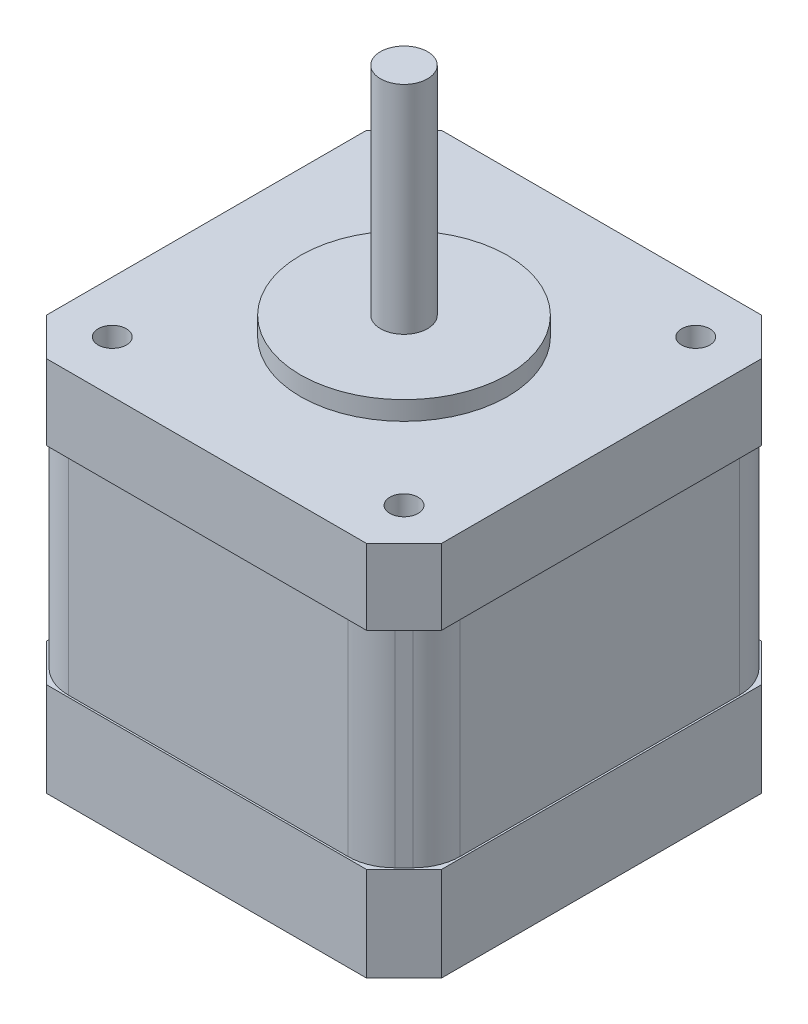
SolidWorks part; units mm, degrees
ref_plane "Front Plane" through (0, 0, 0) normal (0, 0, 1) x (1, 0, 0)
ref_plane "Top Plane" through (0, 0, 0) normal (0, 1, 0) x (1, 0, 0)
ref_plane "Right Plane" through (0, 0, 0) normal (1, 0, 0) x (0, 0, -1)
sketch "Sketch1" plane through (0, 0, 0) normal (0, 1, 0) x (1, 0, 0)
  line L0 (-21, 17) -> (-17, 21)
  line L1 (-17, 21) -> (17, 21)
  line L2 (-21, 17) -> (-21, -17)
  line L3 (-17, -21) -> (17, -21)
  line L4 (21, 17) -> (21, -17)
  line L5 (-21, 21) -> (21, -21) construction
  line L6 (-21, -21) -> (21, 21) construction
  line L7 (-15.5, 15.5) -> (15.5, 15.5) construction
  line L8 (-15.5, 15.5) -> (-15.5, -15.5) construction
  line L9 (-15.5, -15.5) -> (15.5, -15.5) construction
  line L10 (15.5, 15.5) -> (15.5, -15.5) construction
  line L11 (-15.5, 15.5) -> (15.5, -15.5) construction
  line L12 (-15.5, -15.5) -> (15.5, 15.5) construction
  line L13 (17, 21) -> (21, 17)
  line L14 (17, -21) -> (21, -17)
  line L15 (-21, -17) -> (-17, -21)
  line L16 (-20.8, 14.8461) -> (-20.8, -14.8461)
  line L17 (-19.3355, -18.3816) -> (-18.3816, -19.3355)
  line L18 (-14.8461, -20.8) -> (14.8461, -20.8)
  line L19 (18.3816, -19.3355) -> (19.3355, -18.3816)
  line L20 (20.8, 14.8461) -> (20.8, -14.8461)
  line L21 (18.3816, 19.3355) -> (19.3355, 18.3816)
  line L22 (-14.8461, 20.8) -> (14.8461, 20.8)
  line L23 (-19.3355, 18.3816) -> (-18.3816, 19.3355)
  line L24 (16.9172, -20.8) -> (20.8, -16.9172) construction
  line L25 (20.8, 16.9172) -> (20.8, -16.9172) construction
  line L26 (-16.9172, -20.8) -> (16.9172, -20.8) construction
  line L27 (16.9172, 20.8) -> (20.8, 16.9172) construction
  line L28 (-16.9172, 20.8) -> (16.9172, 20.8) construction
  line L29 (-20.8, -16.9172) -> (-16.9172, -20.8) construction
  line L30 (-20.8, 16.9172) -> (-20.8, -16.9172) construction
  line L31 (-20.8, 16.9172) -> (-16.9172, 20.8) construction
  circle A0 centre (-15.5, 15.5) radius 1.5
  circle A1 centre (15.5, 15.5) radius 1.5
  circle A2 centre (15.5, -15.5) radius 1.5
  circle A3 centre (-15.5, -15.5) radius 1.5
  circle A4 centre (0, 0) radius 2.5
  circle A5 centre (0, 0) radius 11
  arc A6 (19.3355, -18.3816) -> (20.8, -14.8461) centre (15.8, -14.8461) ccw
  arc A7 (14.8461, -20.8) -> (18.3816, -19.3355) centre (14.8461, -15.8) ccw
  arc A8 (20.8, 14.8461) -> (19.3355, 18.3816) centre (15.8, 14.8461) ccw
  arc A9 (18.3816, 19.3355) -> (14.8461, 20.8) centre (14.8461, 15.8) ccw
  arc A10 (-18.3816, -19.3355) -> (-14.8461, -20.8) centre (-14.8461, -15.8) ccw
  arc A11 (-20.8, -14.8461) -> (-19.3355, -18.3816) centre (-15.8, -14.8461) ccw
  arc A12 (-20.8, 14.8461) -> (-19.3355, 18.3816) centre (-15.8, 14.8461) cw
  arc A13 (-14.8461, 20.8) -> (-18.3816, 19.3355) centre (-14.8461, 15.8) ccw
  point P0 (0, 0)
  point P6 (0, 0)
  point P21 (0, 0)
  dimension "D4" = 3
  dimension "D6" = 5
  dimension "D7" = 22
  dimension "D13" = 5
  dimension "D1" = 42
  dimension "D2" = 42
  dimension "D3" = 31
  dimension "D12" = 0.2
  dimension "D5" = 4
extrude "Boss-Extrude1" add sketch "Sketch1" along normal blind 10 contours L1 L13 L4 L14 L3 L15 L2 L0
sketch "Sketch2" plane through (0, 10, 0) normal (0, 1, 0) x (1, 0, 0)
  line L0 (-19.3355, 18.3816) -> (-18.3816, 19.3355) construction
  line L1 (-20.8, 14.8461) -> (-20.8, -14.8461) construction
  line L2 (-19.3355, -18.3816) -> (-18.3816, -19.3355) construction
  line L3 (-14.8461, -20.8) -> (14.8461, -20.8) construction
  line L4 (18.3816, -19.3355) -> (19.3355, -18.3816) construction
  line L5 (20.8, 14.8461) -> (20.8, -14.8461) construction
  line L6 (18.3816, 19.3355) -> (19.3355, 18.3816) construction
  line L7 (-14.8461, 20.8) -> (14.8461, 20.8) construction
  line L8 (-19.3355, 18.3816) -> (-18.3816, 19.3355)
  line L9 (-20.8, 14.8461) -> (-20.8, -14.8461)
  line L10 (-19.3355, -18.3816) -> (-18.3816, -19.3355)
  line L11 (-14.8461, -20.8) -> (14.8461, -20.8)
  line L12 (18.3816, -19.3355) -> (19.3355, -18.3816)
  line L13 (20.8, 14.8461) -> (20.8, -14.8461)
  line L14 (18.3816, 19.3355) -> (19.3355, 18.3816)
  line L15 (-14.8461, 20.8) -> (14.8461, 20.8)
  arc A0 (-14.8461, 20.8) -> (-18.3816, 19.3355) centre (-14.8461, 15.8) ccw construction
  arc A1 (-19.3355, 18.3816) -> (-20.8, 14.8461) centre (-15.8, 14.8461) ccw construction
  arc A2 (-20.8, -14.8461) -> (-19.3355, -18.3816) centre (-15.8, -14.8461) ccw construction
  arc A3 (-18.3816, -19.3355) -> (-14.8461, -20.8) centre (-14.8461, -15.8) ccw construction
  arc A4 (14.8461, -20.8) -> (18.3816, -19.3355) centre (14.8461, -15.8) ccw construction
  arc A5 (19.3355, -18.3816) -> (20.8, -14.8461) centre (15.8, -14.8461) ccw construction
  arc A6 (20.8, 14.8461) -> (19.3355, 18.3816) centre (15.8, 14.8461) ccw construction
  arc A7 (18.3816, 19.3355) -> (14.8461, 20.8) centre (14.8461, 15.8) ccw construction
  arc A8 (-14.8461, 20.8) -> (-18.3816, 19.3355) centre (-14.8461, 15.8) ccw
  arc A9 (-19.3355, 18.3816) -> (-20.8, 14.8461) centre (-15.8, 14.8461) ccw
  arc A10 (-20.8, -14.8461) -> (-19.3355, -18.3816) centre (-15.8, -14.8461) ccw
  arc A11 (-18.3816, -19.3355) -> (-14.8461, -20.8) centre (-14.8461, -15.8) ccw
  arc A12 (14.8461, -20.8) -> (18.3816, -19.3355) centre (14.8461, -15.8) ccw
  arc A13 (19.3355, -18.3816) -> (20.8, -14.8461) centre (15.8, -14.8461) ccw
  arc A14 (20.8, 14.8461) -> (19.3355, 18.3816) centre (15.8, 14.8461) ccw
  arc A15 (18.3816, 19.3355) -> (14.8461, 20.8) centre (14.8461, 15.8) ccw
extrude "Boss-Extrude2" add sketch "Sketch2" along normal blind 22
sketch "Sketch3" plane through (0, 32, 0) normal (0, 1, 0) x (1, 0, 0)
  line L8 (-17, 21) -> (-21, 17)
  line L9 (17, 21) -> (-17, 21)
  line L10 (21, 17) -> (17, 21)
  line L11 (21, -17) -> (21, 17)
  line L12 (17, -21) -> (21, -17)
  line L13 (-17, -21) -> (17, -21)
  line L14 (-21, -17) -> (-17, -21)
  line L15 (-21, 17) -> (-21, -17)
  line L16 (-17, 21) -> (-21, 17)
  line L17 (17, 21) -> (-17, 21)
  line L18 (21, 17) -> (17, 21)
  line L19 (21, -17) -> (21, 17)
  line L20 (17, -21) -> (21, -17)
  line L21 (-17, -21) -> (17, -21)
  line L22 (-21, -17) -> (-17, -21)
  line L23 (-21, 17) -> (-21, -17)
  circle A0 centre (-15.5, -15.5) radius 1.5 construction
  circle A1 centre (-15.5, -15.5) radius 1.5
  circle A2 centre (-15.5, -15.5) radius 1.5
  circle A3 centre (-15.5, 15.5) radius 1.5 construction
  circle A4 centre (15.5, -15.5) radius 1.5 construction
  circle A5 centre (15.5, 15.5) radius 1.5 construction
  circle A6 centre (-15.5, 15.5) radius 1.5
  circle A7 centre (-15.5, -15.5) radius 1.5
  circle A8 centre (15.5, -15.5) radius 1.5
  circle A9 centre (15.5, 15.5) radius 1.5
  arc M9 (-14.8461, 20.8) -> (-18.3816, 19.3355) centre (-14.8461, 15.8) ccw
  line M10 (-18.3816, 19.3355) -> (-19.3355, 18.3816)
  arc M11 (-19.3355, 18.3816) -> (-20.8, 14.8461) centre (-15.8, 14.8461) ccw
  line M12 (-20.8, 14.8461) -> (-20.8, -14.8461)
  arc M13 (-20.8, -14.8461) -> (-19.3355, -18.3816) centre (-15.8, -14.8461) ccw
  line M14 (-19.3355, -18.3816) -> (-18.3816, -19.3355)
  arc M15 (-18.3816, -19.3355) -> (-14.8461, -20.8) centre (-14.8461, -15.8) ccw
  line M16 (-14.8461, -20.8) -> (14.8461, -20.8)
  arc M17 (14.8461, -20.8) -> (18.3816, -19.3355) centre (14.8461, -15.8) ccw
  line M18 (18.3816, -19.3355) -> (19.3355, -18.3816)
  arc M19 (19.3355, -18.3816) -> (20.8, -14.8461) centre (15.8, -14.8461) ccw
  line M20 (20.8, -14.8461) -> (20.8, 14.8461)
  arc M21 (20.8, 14.8461) -> (19.3355, 18.3816) centre (15.8, 14.8461) ccw
  line M22 (19.3355, 18.3816) -> (18.3816, 19.3355)
  arc M23 (18.3816, 19.3355) -> (14.8461, 20.8) centre (14.8461, 15.8) ccw
  line M24 (14.8461, 20.8) -> (-14.8461, 20.8)
  dimension "D1" = 0
extrude "Boss-Extrude3" add sketch "Sketch3" along normal blind 8 contours A9 A8 A6 A1 M24 M9 M10 M11 M12 M13 M14 M15 M16 M17 M18 M19 M20 M21 M22 M23 | L16 L23 L22 L21 L20 L19 L18 L17 M9 M24 M23 M22 M21 M20 M19 M18 M17 M16 M15 M14 M13 M12 M11 M10
sketch "Sketch4" plane through (0, 40, 0) normal (0, 1, 0) x (1, 0, 0)
  circle A0 centre (0, 0) radius 2.5 construction
  circle A1 centre (0, 0) radius 11 construction
  circle A2 centre (0, 0) radius 2.5
  circle A3 centre (0, 0) radius 11
extrude "Boss-Extrude4" add sketch "Sketch4" along normal blind 2
sketch "Sketch6" plane through (0, 40, 0) normal (0, 1, 0) x (1, 0, 0)
  circle A1 centre (0, 0) radius 2.5
  circle A2 centre (0, 0) radius 2.5
  dimension "D1" = 0
extrude "Boss-Extrude5" add sketch "Sketch6" along normal blind 25
